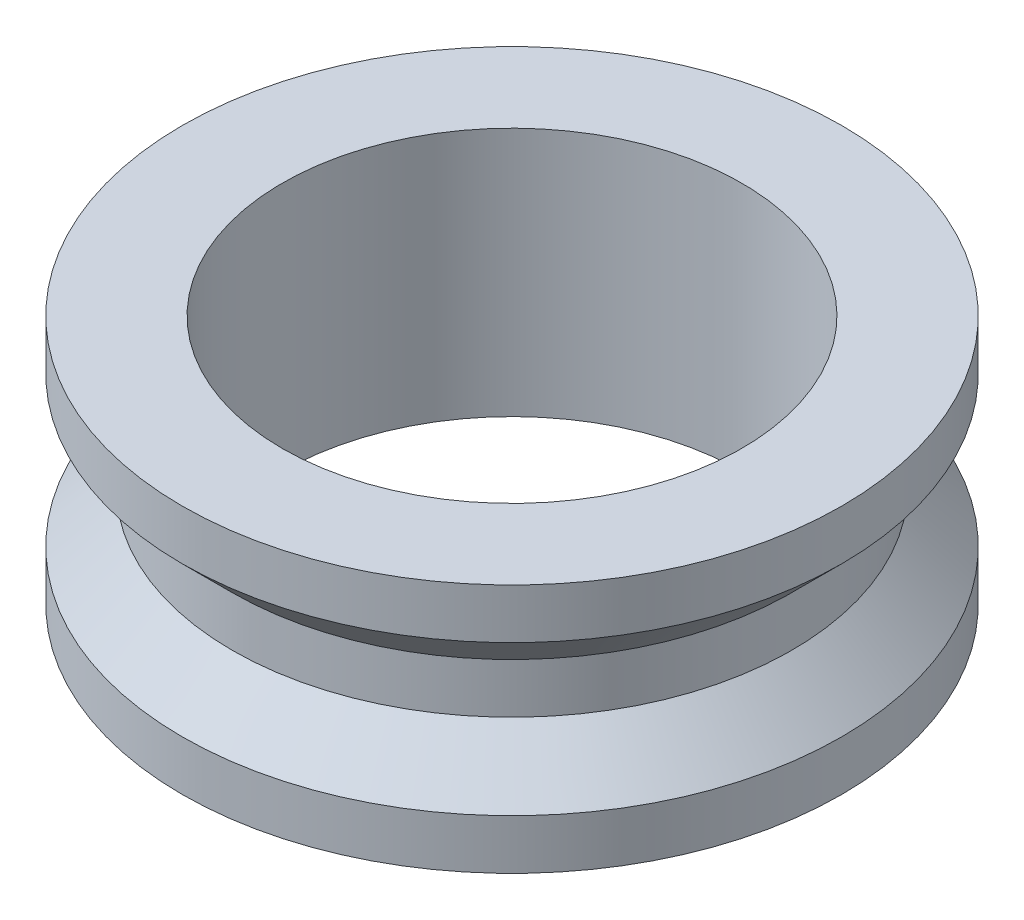
SolidWorks part; units mm, degrees
ref_plane "前视基准面" through (0, 0, 0) normal (0, 0, 1) x (1, 0, 0)
ref_plane "上视基准面" through (0, 0, 0) normal (0, 1, 0) x (1, 0, 0)
ref_plane "右视基准面" through (0, 0, 0) normal (1, 0, 0) x (0, 0, -1)
sketch "草图2" plane through (0, 0, 0) normal (0, 0, 1) x (1, 0, 0)
  line L0 (-4.6, 0) -> (-6.6, 0)
  line L1 (-6.6, 0) -> (-6.6, 1)
  line L2 (-6.6, 1) -> (-5.6, 2)
  line L3 (-5.6, 2) -> (-5.6, 3)
  line L4 (-5.6, 3) -> (-6.6, 4)
  line L5 (-6.6, 4) -> (-6.6, 5)
  line L6 (-6.6, 5) -> (-4.6, 5)
  line L7 (-4.6, 5) -> (-4.6, 0)
  line L8 (0, 5.216) -> (0, -2.3412) construction
  dimension "D1" = 9.2
  dimension "D2" = 2
  dimension "D3" = 5
  dimension "D4" = 45
  dimension "D5" = 45
  dimension "D6" = 1
  dimension "D7" = 1
  dimension "D8" = 1
  dimension "D9" = 5.6
revolve "旋转1" add sketch "草图2" angle 360 about L8
